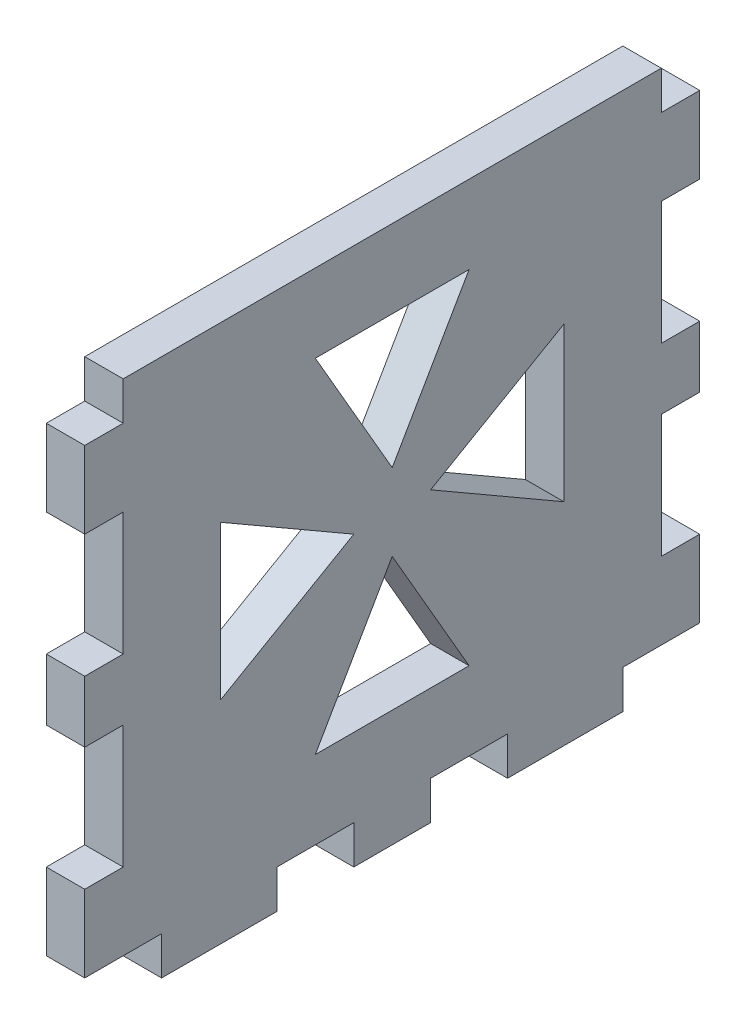
SolidWorks part; units mm, degrees
material "Pine"
ref_plane "Front Plane" through (0, 0, 0) normal (0, 0, 1) x (1, 0, 0)
ref_plane "Top Plane" through (0, 0, 0) normal (0, 1, 0) x (1, 0, 0)
ref_plane "Right Plane" through (0, 0, 0) normal (1, 0, 0) x (0, 0, -1)
sketch "Sketch1" plane through (0, 0, 0) normal (1, 0, 0) x (0, 0, -1)
  line L0 (50.8, 0) -> (50.8, 88.9) construction
  line L1 (0, 0) -> (101.6, 0)
  line L2 (0, 0) -> (0, 88.9)
  line L3 (0, 88.9) -> (101.6, 88.9)
  line L4 (101.6, 0) -> (101.6, 88.9)
  line L5 (0, 0) -> (6.35, 0)
  line L6 (0, 0) -> (0, 6.35)
  line L7 (0, 6.35) -> (6.35, 6.35)
  line L8 (6.35, 0) -> (6.35, 6.35)
  line L9 (101.6, 0) -> (95.25, 0)
  line L10 (101.6, 0) -> (101.6, 6.35)
  line L11 (101.6, 6.35) -> (95.25, 6.35)
  line L12 (95.25, 0) -> (95.25, 6.35)
  line L13 (0, 88.9) -> (6.35, 88.9)
  line L14 (0, 88.9) -> (0, 82.55)
  line L15 (0, 82.55) -> (6.35, 82.55)
  line L16 (6.35, 88.9) -> (6.35, 82.55)
  line L17 (101.6, 88.9) -> (95.25, 88.9)
  line L18 (101.6, 88.9) -> (101.6, 82.55)
  line L19 (101.6, 82.55) -> (95.25, 82.55)
  line L20 (95.25, 88.9) -> (95.25, 82.55)
  line L21 (101.6, 69.85) -> (95.25, 69.85)
  line L22 (101.6, 69.85) -> (101.6, 49.53)
  line L23 (101.6, 49.53) -> (95.25, 49.53)
  line L24 (95.25, 69.85) -> (95.25, 49.53)
  line L25 (101.6, 19.05) -> (95.25, 19.05)
  line L26 (101.6, 19.05) -> (101.6, 39.37)
  line L27 (101.6, 39.37) -> (95.25, 39.37)
  line L28 (95.25, 19.05) -> (95.25, 39.37)
  line L29 (0, 39.37) -> (6.35, 39.37)
  line L30 (6.35, 19.05) -> (6.35, 39.37)
  line L31 (0, 19.05) -> (6.35, 19.05)
  line L32 (0, 19.05) -> (0, 39.37)
  line L33 (0, 49.53) -> (6.35, 49.53)
  line L34 (6.35, 69.85) -> (6.35, 49.53)
  line L35 (0, 69.85) -> (6.35, 69.85)
  line L36 (0, 69.85) -> (0, 49.53)
  line L37 (6.35, 6.35) -> (95.25, 6.35)
  line L39 (12.7, 6.35) -> (31.75, 6.35)
  line L40 (12.7, 6.35) -> (12.7, 0)
  line L41 (12.7, 0) -> (31.75, 0)
  line L42 (31.75, 6.35) -> (31.75, 0)
  line L43 (88.9, 6.35) -> (69.85, 6.35)
  line L44 (88.9, 6.35) -> (88.9, 0)
  line L45 (88.9, 0) -> (69.85, 0)
  line L46 (69.85, 6.35) -> (69.85, 0)
  line L47 (57.15, 6.35) -> (44.45, 6.35)
  line L48 (57.15, 6.35) -> (57.15, 0)
  line L49 (57.15, 0) -> (44.45, 0)
  line L50 (44.45, 6.35) -> (44.45, 0)
  point P25 (98.425, 69.85)
  point P48 (31.75, 3.175)
  dimension "D1" = 101.6
  dimension "D2" = 88.9
  dimension "D3" = 6.35
  dimension "D4" = 6.35
  dimension "D5" = 6.35
  dimension "D6" = 6.35
  dimension "D7" = 6.35
  dimension "D8" = 6.35
  dimension "D9" = 6.35
  dimension "D10" = 6.35
  dimension "D11" = 12.7
  dimension "D12" = 12.7
  dimension "D13" = 20.32
  dimension "D14" = 20.32
  dimension "D15" = 12.7
  dimension "D16" = 12.7
  dimension "D17" = 12.7
  dimension "D18" = 12.7
  dimension "D19" = 12.7
  dimension "D20" = 19.05
extrude "Boss-Extrude1" add sketch "Sketch1" along normal blind 6.35 contours L1 L0 L3 L16 L15 L2 L35 L34 L33 L29 L30 L31 L7 L8 | L0 L1 L12 L11 L4 L25 L28 L27 L23 L24 L21 L19 L20 L3 | L40 L39 L42 L41 | L48 L47 L50 L49 | L44 L43 L46 L45
sketch "Sketch2" plane through (6.35, 0, 0) normal (1, 0, 0) x (0, 0, -1)
  line L0 (50.8, 88.9) -> (50.8, 0) construction
  line L1 (44.45, 47.625) -> (22.453, 60.325)
  line L2 (22.453, 60.325) -> (22.453, 34.925)
  line L3 (22.453, 34.925) -> (44.45, 47.625)
  line L4 (6.35, 88.9) -> (95.25, 88.9) construction
  line L6 (50.8, 53.975) -> (63.5, 75.972)
  line L7 (101.6, 39.37) -> (101.6, 49.53) construction
  line L8 (101.6, 47.625) -> (0, 47.625) construction
  line L9 (0, 39.37) -> (0, 49.53) construction
  line L10 (63.5, 75.972) -> (38.1, 75.972)
  line L11 (38.1, 75.972) -> (50.8, 53.975)
  line L12 (57.15, 47.625) -> (79.147, 34.925)
  line L13 (79.147, 34.925) -> (79.147, 60.325)
  line L14 (79.147, 60.325) -> (57.15, 47.625)
  line L15 (50.8, 41.275) -> (38.1, 19.278)
  line L16 (38.1, 19.278) -> (63.5, 19.278)
  line L17 (63.5, 19.278) -> (50.8, 41.275)
  line L18 (57.15, 0) -> (44.45, 0) construction
  circle A0 centre (29.7853, 47.625) radius 7.3323 construction
  point P20 (50.8, 47.625)
  point P29 (50.8, 47.625)
  dimension "D1" = 6.35
  dimension "=" = 41.275
  dimension "D2" = 4
  dimension "D3" = 25.4
extrude "Cut-Extrude1" cut sketch "Sketch2" against normal up to surface (6.35 mm away) up to face at (0, 35.2778, -50.8)
